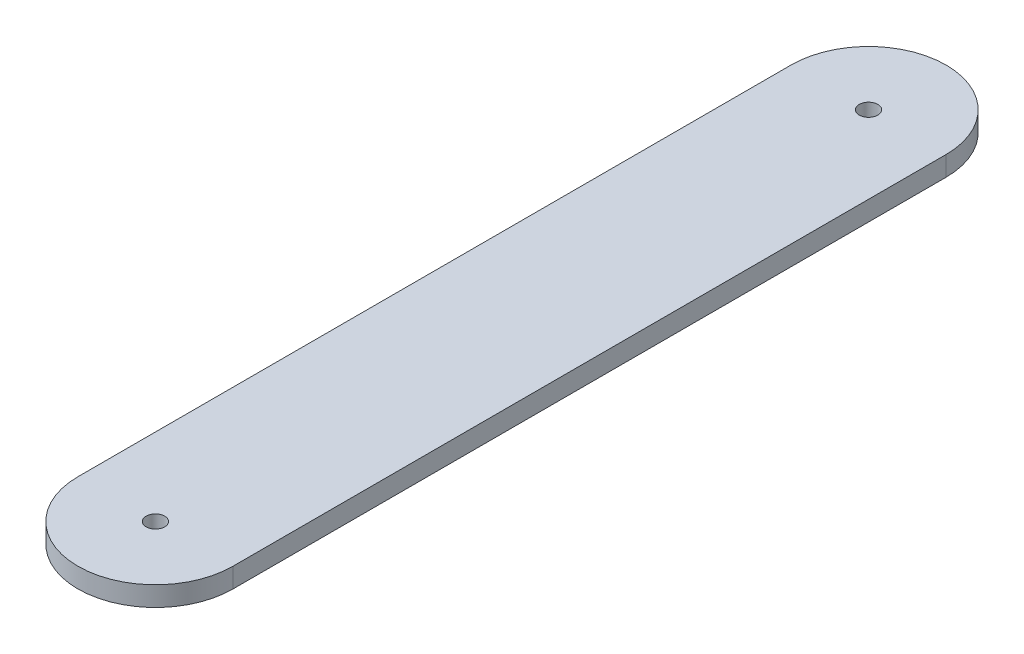
SolidWorks part; units mm, degrees
ref_plane "Front Plane" through (0, 0, 0) normal (0, 0, 1) x (1, 0, 0)
ref_plane "Top Plane" through (0, 0, 0) normal (0, 1, 0) x (1, 0, 0)
ref_plane "Right Plane" through (0, 0, 0) normal (1, 0, 0) x (0, 0, -1)
sketch "Sketch1" plane through (0, 0, 0) normal (0, 1, 0) x (1, 0, 0)
  line L0 (-12.5, 0) -> (-12.5, 115)
  line L1 (12.5, 0) -> (12.5, 115)
  arc A0 (12.5, 0) -> (-12.5, 0) centre (0, 0) cw
  arc A1 (-12.5, 115) -> (12.5, 115) centre (0, 115) cw
  circle A2 centre (0, 115) radius 1.5
  circle A3 centre (0, 0) radius 1.5
  dimension "D2" = 115
  dimension "D3" = 3
  dimension "D4" = 3
  dimension "D1" = 25
extrude "Boss-Extrude1" add sketch "Sketch1" along normal blind 3.18
